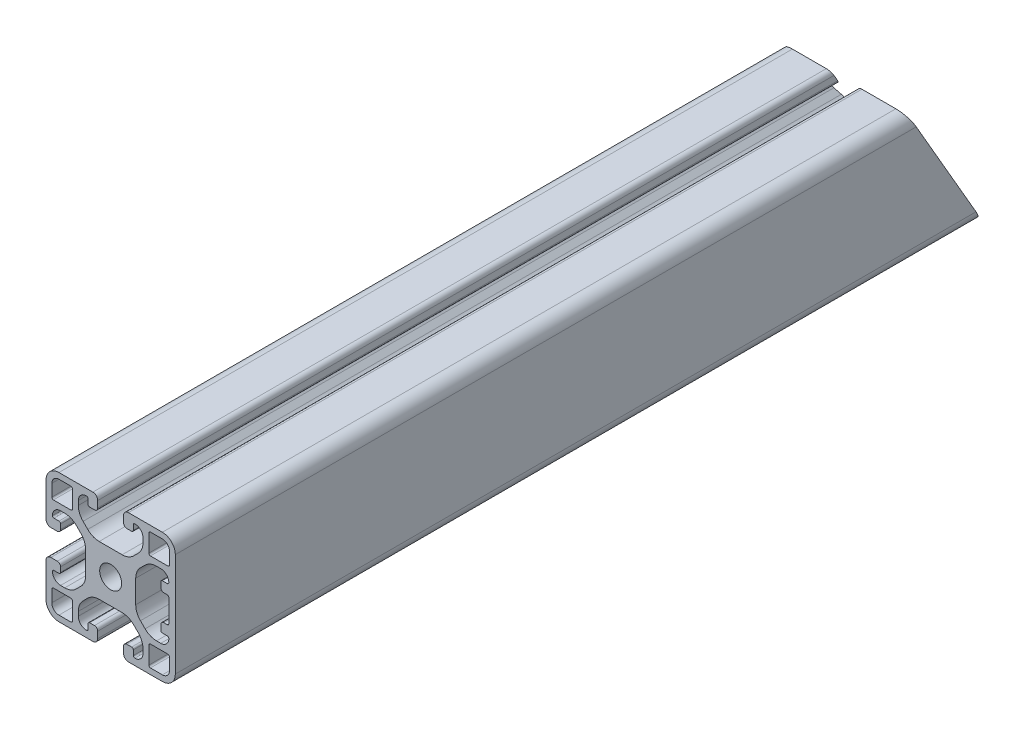
SolidWorks part; units mm, degrees
ref_plane "Piano frontale" through (0, 0, 0) normal (0, 0, 1) x (1, 0, 0)
ref_plane "Piano superiore" through (0, 0, 0) normal (0, 1, 0) x (1, 0, 0)
ref_plane "Piano destro" through (0, 0, 0) normal (1, 0, 0) x (0, 0, -1)
ref_plane "Piano1" through (0, 0, -340) normal (0, 0, -1) x (-1, 0, 0)
sketch "Schizzo1" plane through (0, 0, -340) normal (0, 0, -1) x (-1, 0, 0)
  line L0 (-12.3, -18.2) -> (-16, -18.2)
  line L1 (-18.2, -16) -> (-18.2, -12.3)
  line L2 (-17.7, -11.8) -> (-12.3, -11.8)
  line L3 (-11.8, -12.3) -> (-11.8, -17.7)
  line L4 (-11.8, 17.7) -> (-11.8, 12.3)
  line L5 (-12.3, 11.8) -> (-17.7, 11.8)
  line L6 (-18.2, 12.3) -> (-18.2, 16)
  line L7 (-16, 18.2) -> (-12.3, 18.2)
  line L8 (18.2, 16) -> (18.2, 12.3)
  line L9 (17.7, 11.8) -> (12.3, 11.8)
  line L10 (11.8, 12.3) -> (11.8, 17.7)
  line L11 (12.3, 18.2) -> (16, 18.2)
  line L12 (6.5, -15.5) -> (5, -15.5)
  line L13 (4, -16.5) -> (4, -18.5)
  line L14 (5.5, -20) -> (16, -20)
  line L15 (20, -16) -> (20, -5.5)
  line L16 (18.5, -4) -> (16.5, -4)
  line L17 (15.5, -5) -> (15.5, -6.5)
  line L18 (16, -7) -> (17.55, -7)
  line L19 (18, -7.45) -> (18, -7.5)
  line L20 (15.5, -10) -> (14.1924, -10)
  line L21 (10.6569, -8.5355) -> (9.2145, -7.0931)
  line L22 (7.75, -3.5576) -> (7.75, 3.5576)
  line L23 (9.2145, 7.0931) -> (10.6569, 8.5355)
  line L24 (14.1924, 10) -> (15.5, 10)
  line L25 (18, 7.5) -> (18, 7.45)
  line L26 (17.55, 7) -> (16, 7)
  line L27 (15.5, 6.5) -> (15.5, 5)
  line L28 (16.5, 4) -> (18.5, 4)
  line L29 (20, 5.5) -> (20, 16)
  line L30 (16, 20) -> (5.5, 20)
  line L31 (4, 18.5) -> (4, 16.5)
  line L32 (5, 15.5) -> (6.5, 15.5)
  line L33 (7, 16) -> (7, 17.55)
  line L34 (7.45, 18) -> (7.5, 18)
  line L35 (10, 15.5) -> (10, 14.1924)
  line L36 (8.5355, 10.6569) -> (7.0931, 9.2145)
  line L37 (3.5576, 7.75) -> (-3.5576, 7.75)
  line L38 (-7.0931, 9.2145) -> (-8.5355, 10.6569)
  line L39 (-10, 14.1924) -> (-10, 15.5)
  line L40 (-7.5, 18) -> (-7.45, 18)
  line L41 (-7, 17.55) -> (-7, 16)
  line L42 (-6.5, 15.5) -> (-5, 15.5)
  line L43 (-4, 16.5) -> (-4, 18.5)
  line L44 (-5.5, 20) -> (-16, 20)
  line L45 (-20, 16) -> (-20, -16)
  line L46 (-16, -20) -> (-5.5, -20)
  line L47 (-4, -18.5) -> (-4, -16.5)
  line L48 (-5, -15.5) -> (-6.5, -15.5)
  line L49 (-7, -16) -> (-7, -17.55)
  line L50 (-7.45, -18) -> (-7.5, -18)
  line L51 (-10, -15.5) -> (-10, -14.1924)
  line L52 (-8.5355, -10.6569) -> (-7.0931, -9.2145)
  line L53 (-3.5576, -7.75) -> (3.5576, -7.75)
  line L54 (7.0931, -9.2145) -> (8.5355, -10.6569)
  line L55 (10, -14.1924) -> (10, -15.5)
  line L56 (7.5, -18) -> (7.45, -18)
  line L57 (7, -17.55) -> (7, -16)
  line L58 (18.2, -12.3) -> (18.2, -16)
  line L59 (16, -18.2) -> (12.3, -18.2)
  line L60 (11.8, -17.7) -> (11.8, -12.3)
  line L61 (12.3, -11.8) -> (17.7, -11.8)
  line L62 (-16, 7) -> (-17.5, 7)
  line L63 (-15.5, 10) -> (-14.1924, 10)
  line L64 (-10.6569, 8.5355) -> (-9.2145, 7.0931)
  line L65 (-7.75, 3.5576) -> (-7.75, -3.5576)
  line L66 (-9.2145, -7.0931) -> (-10.6569, -8.5355)
  line L67 (-14.1924, -10) -> (-15.5, -10)
  line L68 (-17.5, -7) -> (-16, -7)
  line L69 (-15.5, -6.5) -> (-15.5, -5)
  line L70 (-16.5, -4) -> (-17.5, -4)
  line L71 (-18, -3.5) -> (-18, 3.5)
  line L72 (-17.5, 4) -> (-16.5, 4)
  line L73 (-15.5, 5) -> (-15.5, 6.5)
  arc A0 (-16, -18.2) -> (-18.2, -16) centre (-16, -16) cw
  arc A1 (-18.2, -12.3) -> (-17.7, -11.8) centre (-17.7, -12.3) cw
  arc A2 (-12.3, -11.8) -> (-11.8, -12.3) centre (-12.3, -12.3) cw
  arc A3 (-11.8, -17.7) -> (-12.3, -18.2) centre (-12.3, -17.7) cw
  arc A4 (-12.3, 18.2) -> (-11.8, 17.7) centre (-12.3, 17.7) cw
  arc A5 (-11.8, 12.3) -> (-12.3, 11.8) centre (-12.3, 12.3) cw
  arc A6 (-17.7, 11.8) -> (-18.2, 12.3) centre (-17.7, 12.3) cw
  arc A7 (-18.2, 16) -> (-16, 18.2) centre (-16, 16) cw
  arc A8 (16, 18.2) -> (18.2, 16) centre (16, 16) cw
  arc A9 (18.2, 12.3) -> (17.7, 11.8) centre (17.7, 12.3) cw
  arc A10 (12.3, 11.8) -> (11.8, 12.3) centre (12.3, 12.3) cw
  arc A11 (11.8, 17.7) -> (12.3, 18.2) centre (12.3, 17.7) cw
  arc A12 (5, -15.5) -> (4, -16.5) centre (5, -16.5) ccw
  arc A13 (4, -18.5) -> (5.5, -20) centre (5.5, -18.5) ccw
  arc A14 (16, -20) -> (20, -16) centre (16, -16) ccw
  arc A15 (20, -5.5) -> (18.5, -4) centre (18.5, -5.5) ccw
  arc A16 (16.5, -4) -> (15.5, -5) centre (16.5, -5) ccw
  arc A17 (15.5, -6.5) -> (16, -7) centre (16, -6.5) ccw
  arc A18 (17.55, -7) -> (18, -7.45) centre (17.55, -7.45) cw
  arc A19 (18, -7.5) -> (15.5, -10) centre (15.5, -7.5) cw
  arc A20 (14.1924, -10) -> (10.6569, -8.5355) centre (14.1924, -5) cw
  arc A21 (9.2145, -7.0931) -> (7.75, -3.5576) centre (12.75, -3.5576) cw
  arc A22 (7.75, 3.5576) -> (9.2145, 7.0931) centre (12.75, 3.5576) cw
  arc A23 (10.6569, 8.5355) -> (14.1924, 10) centre (14.1924, 5) cw
  arc A24 (15.5, 10) -> (18, 7.5) centre (15.5, 7.5) cw
  arc A25 (18, 7.45) -> (17.55, 7) centre (17.55, 7.45) cw
  arc A26 (16, 7) -> (15.5, 6.5) centre (16, 6.5) ccw
  arc A27 (15.5, 5) -> (16.5, 4) centre (16.5, 5) ccw
  arc A28 (18.5, 4) -> (20, 5.5) centre (18.5, 5.5) ccw
  arc A29 (20, 16) -> (16, 20) centre (16, 16) ccw
  arc A30 (5.5, 20) -> (4, 18.5) centre (5.5, 18.5) ccw
  arc A31 (4, 16.5) -> (5, 15.5) centre (5, 16.5) ccw
  arc A32 (6.5, 15.5) -> (7, 16) centre (6.5, 16) ccw
  arc A33 (7, 17.55) -> (7.45, 18) centre (7.45, 17.55) cw
  arc A34 (7.5, 18) -> (10, 15.5) centre (7.5, 15.5) cw
  arc A35 (10, 14.1924) -> (8.5355, 10.6569) centre (5, 14.1924) cw
  arc A36 (7.0931, 9.2145) -> (3.5576, 7.75) centre (3.5576, 12.75) cw
  arc A37 (-3.5576, 7.75) -> (-7.0931, 9.2145) centre (-3.5576, 12.75) cw
  arc A38 (-8.5355, 10.6569) -> (-10, 14.1924) centre (-5, 14.1924) cw
  arc A39 (-10, 15.5) -> (-7.5, 18) centre (-7.5, 15.5) cw
  arc A40 (-7.45, 18) -> (-7, 17.55) centre (-7.45, 17.55) cw
  arc A41 (-7, 16) -> (-6.5, 15.5) centre (-6.5, 16) ccw
  arc A42 (-5, 15.5) -> (-4, 16.5) centre (-5, 16.5) ccw
  arc A43 (-4, 18.5) -> (-5.5, 20) centre (-5.5, 18.5) ccw
  arc A44 (-16, 20) -> (-20, 16) centre (-16, 16) ccw
  arc A45 (-20, -16) -> (-16, -20) centre (-16, -16) ccw
  arc A46 (-5.5, -20) -> (-4, -18.5) centre (-5.5, -18.5) ccw
  arc A47 (-4, -16.5) -> (-5, -15.5) centre (-5, -16.5) ccw
  arc A48 (-6.5, -15.5) -> (-7, -16) centre (-6.5, -16) ccw
  arc A49 (-7, -17.55) -> (-7.45, -18) centre (-7.45, -17.55) cw
  arc A50 (-7.5, -18) -> (-10, -15.5) centre (-7.5, -15.5) cw
  arc A51 (-10, -14.1924) -> (-8.5355, -10.6569) centre (-5, -14.1924) cw
  arc A52 (-7.0931, -9.2145) -> (-3.5576, -7.75) centre (-3.5576, -12.75) cw
  arc A53 (3.5576, -7.75) -> (7.0931, -9.2145) centre (3.5576, -12.75) cw
  arc A54 (8.5355, -10.6569) -> (10, -14.1924) centre (5, -14.1924) cw
  arc A55 (10, -15.5) -> (7.5, -18) centre (7.5, -15.5) cw
  arc A56 (7.45, -18) -> (7, -17.55) centre (7.45, -17.55) cw
  arc A57 (7, -16) -> (6.5, -15.5) centre (6.5, -16) ccw
  arc A58 (17.7, -11.8) -> (18.2, -12.3) centre (17.7, -12.3) cw
  arc A59 (18.2, -16) -> (16, -18.2) centre (16, -16) cw
  arc A60 (12.3, -18.2) -> (11.8, -17.7) centre (12.3, -17.7) cw
  arc A61 (11.8, -12.3) -> (12.3, -11.8) centre (12.3, -12.3) cw
  circle A62 centre (0, 0) radius 3.4
  arc A63 (-15.5, 6.5) -> (-16, 7) centre (-16, 6.5) ccw
  arc A64 (-17.5, 7) -> (-18, 7.5) centre (-17.5, 7.5) cw
  arc A65 (-18, 7.5) -> (-15.5, 10) centre (-15.5, 7.5) cw
  arc A66 (-14.1924, 10) -> (-10.6569, 8.5355) centre (-14.1924, 5) cw
  arc A67 (-9.2145, 7.0931) -> (-7.75, 3.5576) centre (-12.75, 3.5576) cw
  arc A68 (-7.75, -3.5576) -> (-9.2145, -7.0931) centre (-12.75, -3.5576) cw
  arc A69 (-10.6569, -8.5355) -> (-14.1924, -10) centre (-14.1924, -5) cw
  arc A70 (-15.5, -10) -> (-18, -7.5) centre (-15.5, -7.5) cw
  arc A71 (-18, -7.5) -> (-17.5, -7) centre (-17.5, -7.5) cw
  arc A72 (-16, -7) -> (-15.5, -6.5) centre (-16, -6.5) ccw
  arc A73 (-15.5, -5) -> (-16.5, -4) centre (-16.5, -5) ccw
  arc A74 (-17.5, -4) -> (-18, -3.5) centre (-17.5, -3.5) cw
  arc A75 (-18, 3.5) -> (-17.5, 4) centre (-17.5, 3.5) cw
  arc A76 (-16.5, 4) -> (-15.5, 5) centre (-16.5, 5) ccw
extrude "Estrusione-Estrusione1" add sketch "Schizzo1" against normal blind 250
sketch "Schizzo9" plane through (20, 0, 0) normal (1, 0, 0) x (0, 0, -1)
  line L0 (340, -16) -> (340, 16) construction
  line L1 (90, 16) -> (90, -16) construction
  line L2 (340, 16) -> (340, 20) construction
  line L3 (340, 20) -> (90, 20) construction
  line L4 (90, 20) -> (90, 16) construction
  line L5 (340, -20) -> (340, -16) construction
  line L6 (90, -16) -> (90, -20) construction
  line L7 (90, -20) -> (340, -20) construction
  line L8 (340, -16) -> (340, 16)
  line L9 (90, 16) -> (90, -16)
  line L10 (340, 16) -> (340, 20)
  line L11 (340, 20) -> (90, 20)
  line L12 (90, 20) -> (90, 16)
  line L13 (340, -20) -> (340, -16)
  line L14 (90, -16) -> (90, -20)
  line L15 (90, -20) -> (340, -20)
  line L16 (-536.8844, 20) -> (-536.8844, -20)
  line L17 (-536.8844, -20) -> (90, 20)
  line L18 (316.8895, -20) -> (316.8895, 20)
  line L19 (340, -20) -> (316.8895, 20)
  line L20 (90, 20) -> (113.1565, -20)
  line M1 (340, -16) -> (340, 16)
  line M2 (340, 16) -> (90, 16)
  line M4 (90, -16) -> (340, -16)
extrude "Taglio-Estrusione1" cut sketch "Schizzo9" against normal through all contours L19 M4 M1 M2 | L19 L13 M4 | L19 L10 L11 M2 | L12 L9 L14 L15
